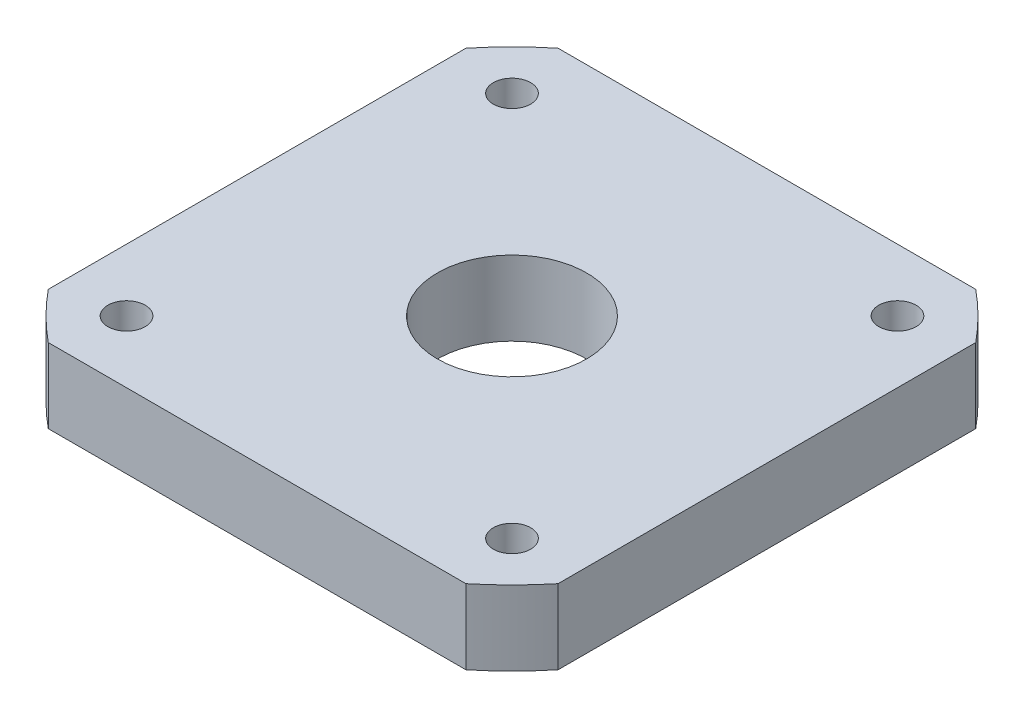
SolidWorks part; units mm, degrees
ref_plane "Front Plane" through (0, 0, 0) normal (0, 0, 1) x (1, 0, 0)
ref_plane "Top Plane" through (0, 0, 0) normal (0, 1, 0) x (1, 0, 0)
ref_plane "Right Plane" through (0, 0, 0) normal (1, 0, 0) x (0, 0, -1)
sketch "Plate Base" plane through (0, 0, 0) normal (0, 1, 0) x (1, 0, 0)
  line L4 (16.7929, 20.5) -> (-16.7929, 20.5)
  line L5 (-20.5, 16.7929) -> (-20.5, -16.7929)
  line L6 (-16.7929, -20.5) -> (16.7929, -20.5)
  line L7 (20.5, -16.7929) -> (20.5, 16.7929)
  line L8 (16.7929, 20.5) -> (-16.7929, 20.5)
  line L9 (-20.5, 16.7929) -> (-20.5, -16.7929)
  line L10 (-16.7929, -20.5) -> (16.7929, -20.5)
  line L11 (20.5, -16.7929) -> (20.5, 16.7929)
  circle A0 centre (0, 0) radius 6
  arc A4 (-16.7929, 20.5) -> (-20.5, 16.7929) centre (0, 0) ccw
  arc A5 (-20.5, -16.7929) -> (-16.7929, -20.5) centre (0, 0) ccw
  arc A6 (16.7929, -20.5) -> (20.5, -16.7929) centre (0, 0) ccw
  arc A7 (20.5, 16.7929) -> (16.7929, 20.5) centre (0, 0) ccw
  arc A8 (-16.7929, 20.5) -> (-20.5, 16.7929) centre (0, 0) ccw
  arc A9 (-20.5, -16.7929) -> (-16.7929, -20.5) centre (0, 0) ccw
  arc A10 (16.7929, -20.5) -> (20.5, -16.7929) centre (0, 0) ccw
  arc A11 (20.5, 16.7929) -> (16.7929, 20.5) centre (0, 0) ccw
  circle A16 centre (15.5, 15.5) radius 1.5
  circle A17 centre (-15.5, 15.5) radius 1.5
  circle A19 centre (-15.5, -15.5) radius 1.5
  circle A20 centre (15.5, -15.5) radius 1.5
  dimension "D2" = 3
  dimension "D3" = 3
  dimension "D4" = 3
  dimension "D5" = 3
  dimension "D15" = 12
  dimension "D6" = 5
  dimension "D7" = 5
  dimension "D8" = 5
  dimension "D9" = 5
  dimension "D10" = 33.5857
  dimension "D11" = 31
  dimension "D12" = 5
  dimension "D13" = 5
  dimension "D14" = 31
  dimension "D1" = 0
extrude "Housing" add sketch "Plate Base" along normal blind 6
sketch "Sketch4" plane through (0, 6, 0) normal (0, 1, 0) x (1, 0, 0)
  circle A1 centre (0, 0) radius 18.5
  circle A2 centre (0, 0) radius 16
  dimension "D1" = 37
  dimension "D2" = 2.5
